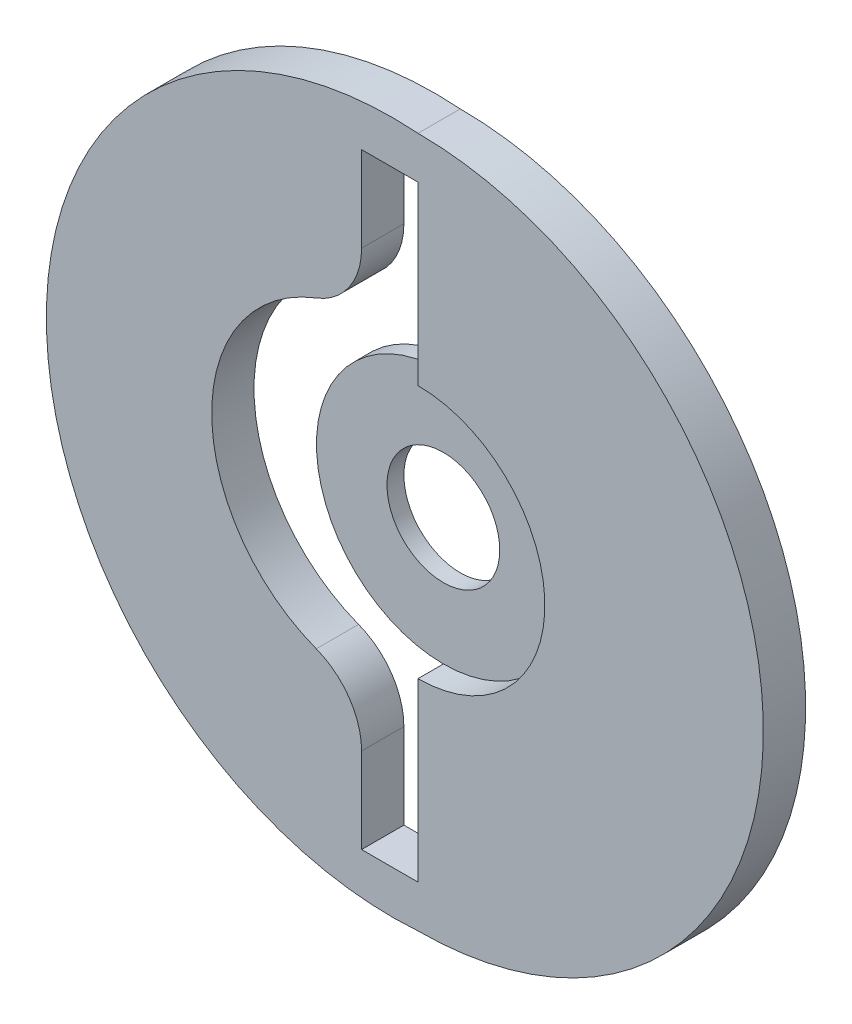
SolidWorks part; units mm, degrees
ref_plane "Alzado" through (0, 0, 0) normal (0, 0, 1) x (1, 0, 0)
ref_plane "Planta" through (0, 0, 0) normal (0, 1, 0) x (1, 0, 0)
ref_plane "Vista lateral" through (0, 0, 0) normal (1, 0, 0) x (0, 0, -1)
sketch "Croquis1" plane through (0, 0, 0) normal (0, 0, 1) x (1, 0, 0)
  line L1 (-39.3104, -0.627) -> (-39.3104, 19.873)
  line L2 (-39.3104, -8.627) -> (-39.3104, -29.127)
  arc A0 (-39.3104, 19.873) -> (-39.3104, -29.127) centre (-39.3104, -4.627) cw
  arc A3 (-39.3104, -0.627) -> (-39.3104, -8.627) centre (-39.3104, -4.627) cw
  dimension "D2" = 4
  dimension "D1" = 49
  dimension "D3" = 20.5
extrude "Saliente-Extruir1" add sketch "Croquis1" along normal blind 3
sketch "Croquis2" plane through (0, 0, 3) normal (0, 0, 1) x (1, 0, 0)
  circle A0 centre (-39.3104, -4.627) radius 9
  dimension "D1" = 18
extrude "Cortar-Extruir1" cut sketch "Croquis2" against normal blind 1.8
sketch "Croquis3" plane through (0, 0, 1.2) normal (0, 0, 1) x (1, 0, 0)
  line L0 (-39.3104, 4.373) -> (-39.3104, -0.627) construction
  line L1 (-39.3104, 4.373) -> (-39.3104, -0.627)
  line L2 (-39.3104, -8.627) -> (-39.3104, -13.627)
  arc A1 (-39.3104, -13.627) -> (-39.3104, 4.373) centre (-39.3104, -4.627) ccw construction
  arc A3 (-39.3104, -8.627) -> (-39.3104, -0.627) centre (-39.3104, -4.627) ccw construction
  arc A5 (-39.3104, -0.627) -> (-39.3104, -8.627) centre (-39.3104, -4.627) ccw
  arc A6 (-39.3104, 4.373) -> (-39.3104, -13.627) centre (-39.3104, -4.627) ccw
extrude "Saliente-Extruir2" add sketch "Croquis3" against normal up to vertex (1.2 mm away)
sketch "Croquis4" plane through (0, 0, 3) normal (0, 0, 1) x (1, 0, 0)
  line L0 (-39.3104, 19.873) -> (-39.3104, 16.873)
  line L1 (-39.3104, 19.873) -> (-39.3104, 4.373) construction
  line L2 (-39.3104, 16.873) -> (-43.3104, 16.873)
  line L4 (-39.3104, -13.627) -> (-39.3104, -29.127) construction
  line L5 (-39.3104, -29.127) -> (-39.3104, -26.127)
  line L6 (-39.3104, -26.127) -> (-43.3104, -26.127)
  line L8 (-43.3104, 16.873) -> (-43.3104, 6.873)
  line L9 (-43.3104, -26.127) -> (-43.3104, -16.127)
  arc A4 (-43.3104, 6.873) -> (-43.3104, -16.127) centre (-42.4078, -4.627) ccw
  arc A5 (-39.3104, 19.873) -> (-39.3104, -29.127) centre (-41.1074, -4.627) ccw
  dimension "D1" = 3
  dimension "D2" = 4
  dimension "D3" = 3
  dimension "D4" = 10
  dimension "D5" = 10
  dimension "D6" = 4
extrude "Saliente-Extruir3" add sketch "Croquis4" against normal up to vertex (3 mm away)
fillet "Redondeo1" radius 5 2 edges at (-43.3104, -16.127, 1.5) (-43.3104, 6.873, 1.5)
